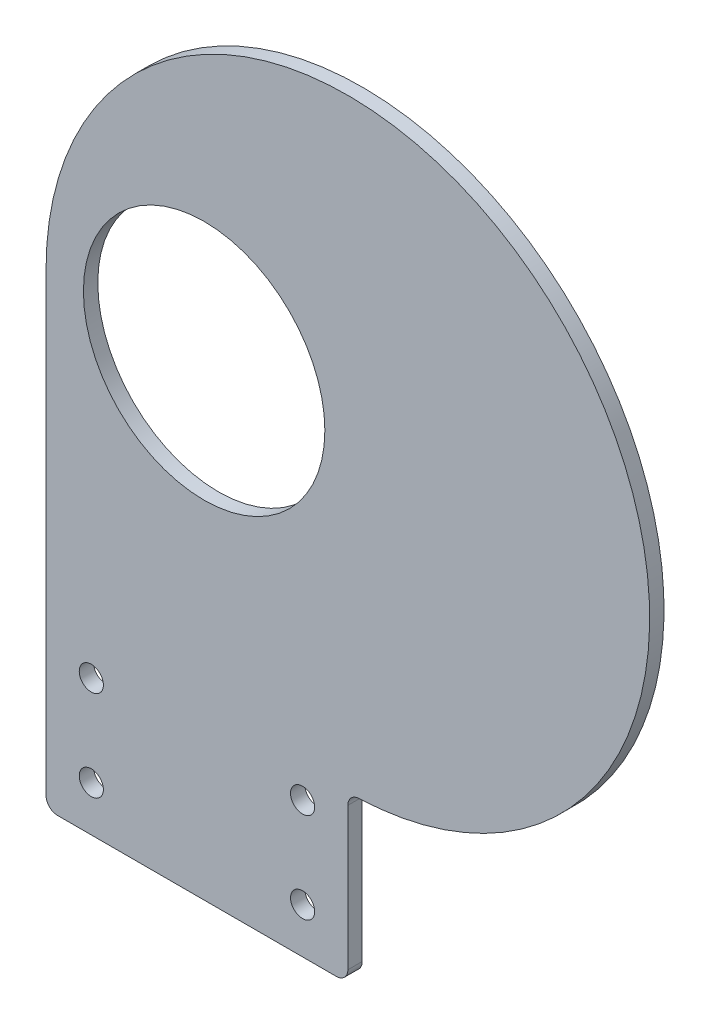
SolidWorks part; units mm, degrees
ref_plane "Front Plane" through (0, 0, 0) normal (0, 0, 1) x (1, 0, 0)
ref_plane "Top Plane" through (0, 0, 0) normal (0, 1, 0) x (1, 0, 0)
ref_plane "Right Plane" through (0, 0, 0) normal (1, 0, 0) x (0, 0, -1)
sketch "Sketch1" plane through (0, 0, 0) normal (0, 0, 1) x (1, 0, 0)
  line L0 (0, 0) -> (31.75, 0) construction
  line L1 (-34.925, 0) -> (-34.925, -63.5)
  line L4 (98.425, -64.8339) -> (98.425, 0)
  line L7 (-34.925, -63.5) -> (-34.925, -103.175)
  line L8 (-34.925, -103.175) -> (98.425, -103.175)
  line L9 (98.425, -64.8339) -> (98.425, -103.175)
  line L10 (-34.925, -63.5) -> (98.425, -103.175) construction
  line L11 (-34.925, -103.175) -> (98.425, -64.8339) construction
  circle A0 centre (0, 0) radius 25.4 construction
  circle A1 centre (0, 0) radius 26.67
  circle A2 centre (31.75, 0) radius 63.5 construction
  arc A3 (98.425, 0) -> (-34.925, 0) centre (31.75, 0) ccw
  circle A4 centre (31.75, 0) radius 66.675 construction
  point P16 (32.89, -83.6767)
  dimension "D1" = 50.8
  dimension "D3" = 127
  dimension "D6" = 103.175
  dimension "D4" = 31.75
  dimension "D2" = 1.27
  dimension "D5" = 3.175
extrude "Boss-Extrude1" add sketch "Sketch1" along normal blind 3.175
sketch "Sketch2" plane through (0, 0, 3.175) normal (0, 0, 1) x (1, 0, 0)
  line L0 (31.75, -66.675) -> (31.75, -103.175)
  line L1 (-34.925, -103.175) -> (98.425, -103.175) construction
  line L2 (31.75, -103.175) -> (98.425, -103.175)
  line L3 (98.425, -103.175) -> (98.425, 0)
  arc A0 (31.75, -66.675) -> (98.425, 0) centre (31.75, 0) ccw
extrude "Cut-Extrude1" cut sketch "Sketch2" against normal up to next
sketch "Sketch3" plane through (0, 0, 0) normal (0, 0, -1) x (-1, 0, 0)
  line L0 (-31.75, -93.175) -> (34.925, -93.175) construction
  line L1 (-31.75, -103.175) -> (-31.75, -66.675) construction
  line L2 (34.925, 0) -> (34.925, -103.175) construction
  line L3 (-31.75, -73.175) -> (34.925, -73.175) construction
  line L4 (34.925, -103.175) -> (-31.75, -103.175) construction
  line L5 (1.5875, -93.175) -> (1.5875, -73.175) construction
  line L6 (1.5875, -83.175) -> (-26.4696, -83.175) construction
  circle A0 centre (-21.75, -93.175) radius 2.665
  circle A1 centre (-21.75, -73.175) radius 2.665
  circle A2 centre (24.925, -93.175) radius 2.665
  circle A3 centre (24.925, -73.175) radius 2.665
  dimension "D3" = 5.33
  dimension "D4" = 10
  dimension "D1" = 20
  dimension "D2" = 10
extrude "Cut-Extrude2" cut sketch "Sketch3" against normal up to next
fillet "Fillet1" radius 2.54 3 edges at (-34.925, -103.175, 1.5875) (31.75, -103.175, 1.5875) (31.75, -66.675, 1.5875)
